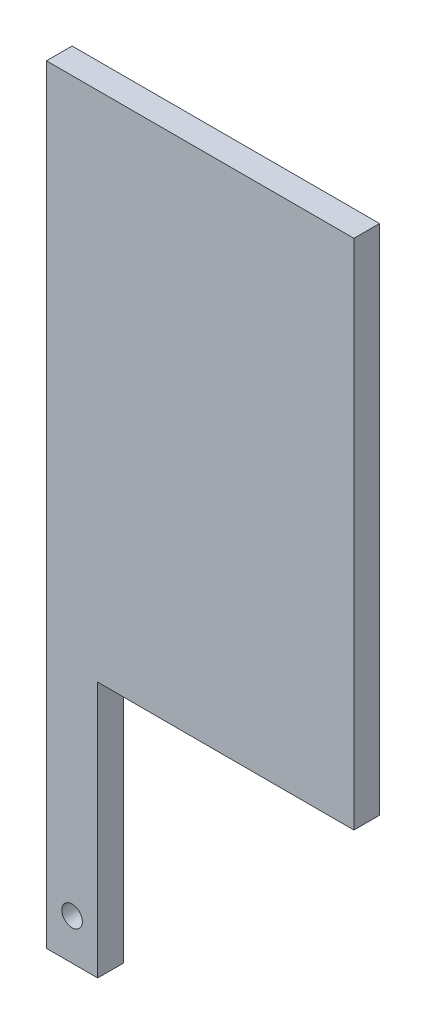
SolidWorks part; units mm, degrees
ref_plane "Plan de face" through (0, 0, 0) normal (0, 0, 1) x (1, 0, 0)
ref_plane "Plan de dessus" through (0, 0, 0) normal (0, 1, 0) x (1, 0, 0)
ref_plane "Plan de droite" through (0, 0, 0) normal (1, 0, 0) x (0, 0, -1)
sketch "Esquisse1" plane through (0, 0, 0) normal (0, 0, 1) x (1, 0, 0)
  line L0 (0, -50) -> (60, -50)
  line L1 (0, 0) -> (60, 0)
  line L2 (0, 0) -> (0, -100)
  line L3 (0, -100) -> (60, -100)
  line L4 (60, 0) -> (60, -100)
  line L5 (0, -100) -> (0, -150)
  line L6 (0, -150) -> (10, -150)
  line L7 (10, -150) -> (10, -100)
  line L8 (0, -150) -> (0, -100)
  dimension "D1" = 50
  dimension "D2" = 10
  dimension "D3" = 100
  dimension "D4" = 60
extrude "Boss.-Extru.1" add sketch "Esquisse1" along normal blind 5 contours L6 L7 L3 L5 | L4 L0 L2 L3
sketch "Esquisse2" plane through (0, 0, 5) normal (0, 0, 1) x (1, 0, 0)
  line L0 (0, -50) -> (0, 0)
  line L1 (0, 0) -> (60, 0)
  line L2 (60, 0) -> (60, -50)
  line L3 (60, -50) -> (60, -100) construction
  line L4 (0, -50) -> (60, -50) construction
  line L5 (0, -50) -> (60, -50)
extrude "Boss.-Extru.2" add sketch "Esquisse2" against normal blind 5
sketch "Esquisse3" plane through (0, 0, 5) normal (0, 0, 1) x (1, 0, 0)
  line L0 (0, -150) -> (10, -150) construction
  line L1 (0, 0) -> (0, -150) construction
  circle A0 centre (5, -142) radius 2
  dimension "D1" = 4
  dimension "D2" = 8
  dimension "D3" = 5
extrude "Enlèv. mat.-Extru.1" cut sketch "Esquisse3" against normal blind 5
